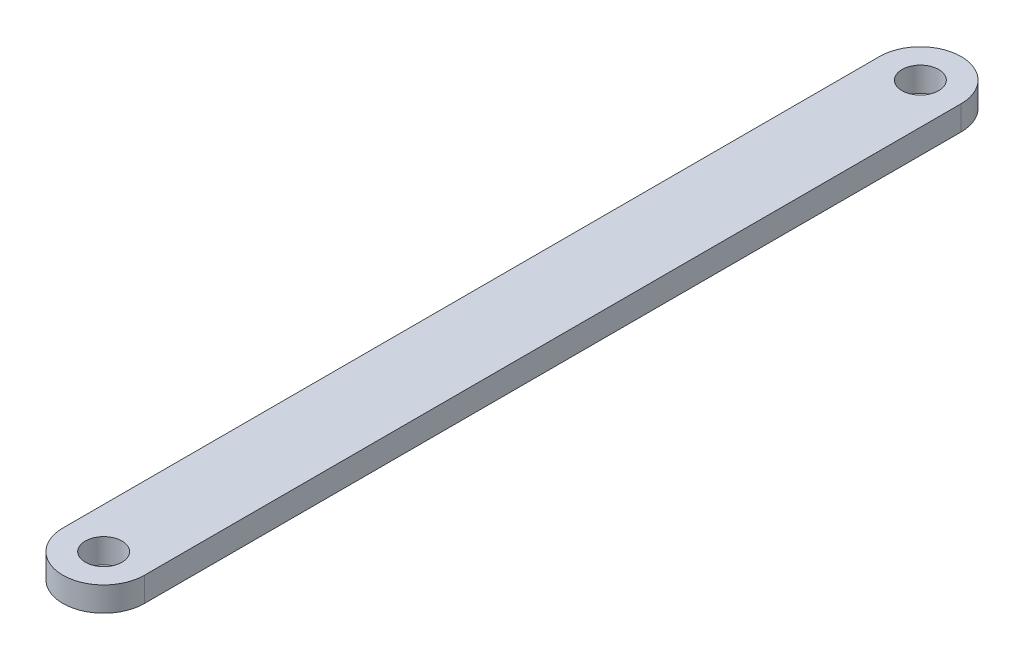
SolidWorks part; units mm, degrees
ref_plane "前视基准面" through (0, 0, 0) normal (0, 0, 1) x (1, 0, 0)
ref_plane "上视基准面" through (0, 0, 0) normal (0, 1, 0) x (1, 0, 0)
ref_plane "右视基准面" through (0, 0, 0) normal (1, 0, 0) x (0, 0, -1)
sketch "草图1" plane through (0, 0, 0) normal (0, 1, 0) x (1, 0, 0)
  line L0 (0, 0) -> (0, -100) construction
  line L1 (5, 0) -> (5, -100)
  line L2 (-5, 0) -> (-5, -100)
  arc A0 (5, 0) -> (-5, 0) centre (0, 0) ccw
  arc A1 (-5, -100) -> (5, -100) centre (0, -100) ccw
  circle A2 centre (0, 0) radius 2.25
  circle A3 centre (0, -100) radius 2.25
  point P3 (0, -50)
  dimension "D2" = 4.5
  dimension "D3" = 4.5
  dimension "D4" = 5
  dimension "D1" = 100
extrude "凸台-拉伸1" add sketch "草图1" along normal blind 3
